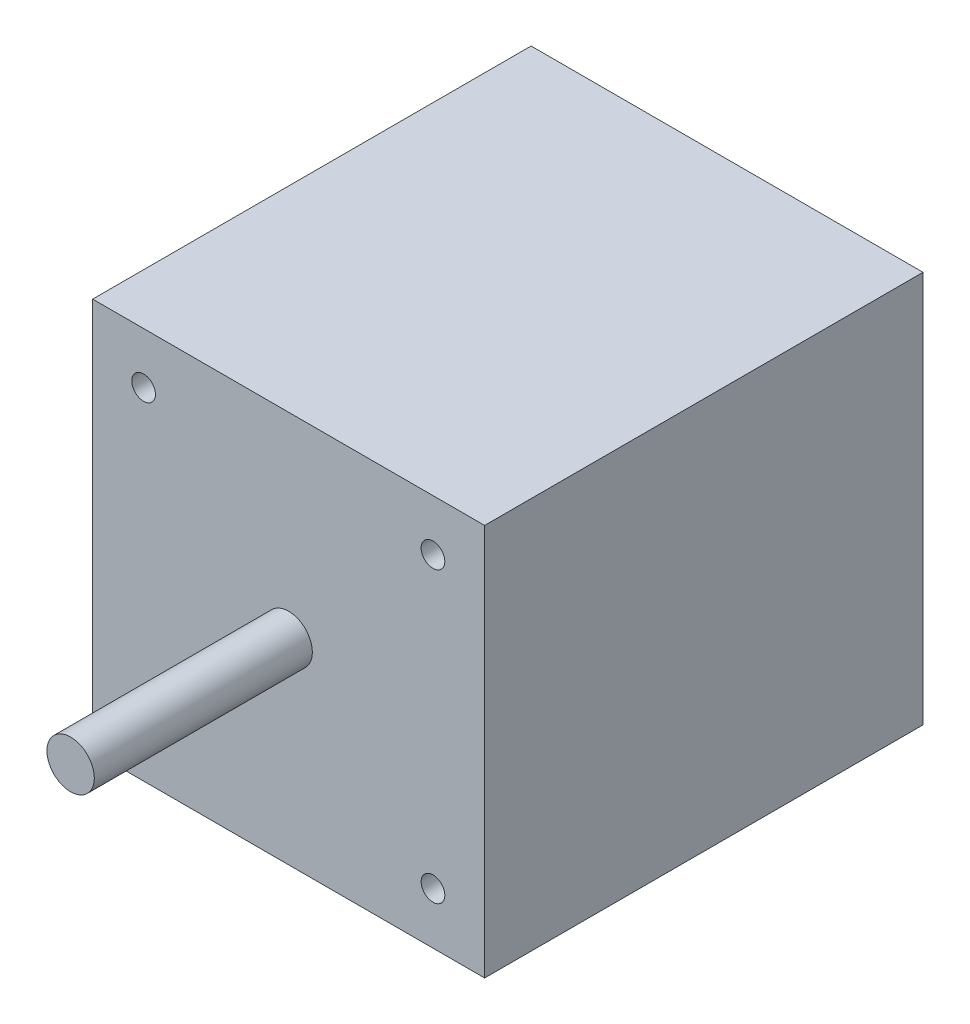
SolidWorks part; units mm, degrees
ref_plane "Front" through (0, 0, 0) normal (0, 0, 1) x (1, 0, 0)
ref_plane "Top" through (0, 0, 0) normal (0, 1, 0) x (1, 0, 0)
ref_plane "Right" through (0, 0, 0) normal (1, 0, 0) x (0, 0, -1)
sketch "Sketch1" plane through (0, 0, 0) normal (0, 0, 1) x (1, 0, 0)
  line L1 (-21.0058, 21.005) -> (21.0058, 21.005)
  line L2 (-21.0058, 21.005) -> (-21.0058, -21.005)
  line L3 (-21.0058, -21.005) -> (21.0058, -21.005)
  line L4 (21.0058, 21.005) -> (21.0058, -21.005)
  line L5 (-21.0058, 21.005) -> (21.0058, -21.005) construction
  line L6 (-21.0058, -21.005) -> (21.0058, 21.005) construction
  point P0 (0, 0)
  dimension "D1" = 42.0116
  dimension "D2" = 42.01
extrude "Boss-Extrude1" add sketch "Sketch1" along normal mid plane 46.99
sketch "Sketch2" plane through (0, 0, 23.495) normal (0, 0, 1) x (1, 0, 0)
  circle A0 centre (0, 0) radius 2.54
  dimension "D1" = 5.08
extrude "Boss-Extrude2" add sketch "Sketch2" along normal blind 23.368
sketch "Sketch3" plane through (0, 0, 23.495) normal (0, 0, 1) x (1, 0, 0)
  line L1 (21.0058, 21.005) -> (-21.0058, 21.005) construction
  line L3 (-21.0058, 21.005) -> (-21.0058, -21.005) construction
  line L5 (-15.5448, 15.5186) -> (15.4686, 15.5186) construction
  line L6 (-15.5448, 15.5186) -> (-15.5448, -15.4678) construction
  line L7 (-15.5448, -15.4678) -> (15.4686, -15.4678) construction
  line L8 (15.4686, 15.5186) -> (15.4686, -15.4678) construction
  line L9 (-21.0058, -21.005) -> (21.0058, -21.005) construction
  line L10 (21.0058, -21.005) -> (21.0058, 21.005) construction
  circle A0 centre (15.4686, -15.4678) radius 1.27
  circle A1 centre (-15.5448, 15.5186) radius 1.27
  circle A2 centre (15.4686, 15.5186) radius 1.27
  circle A3 centre (-15.5448, -15.4678) radius 1.27
  dimension "D1" = 4.2164
  dimension "D2" = 4.191
  dimension "D3" = 2.54
  dimension "D4" = 4.2672
  dimension "D5" = 4.2672
extrude "Cut-Extrude1" cut sketch "Sketch3" against normal blind 5.588
